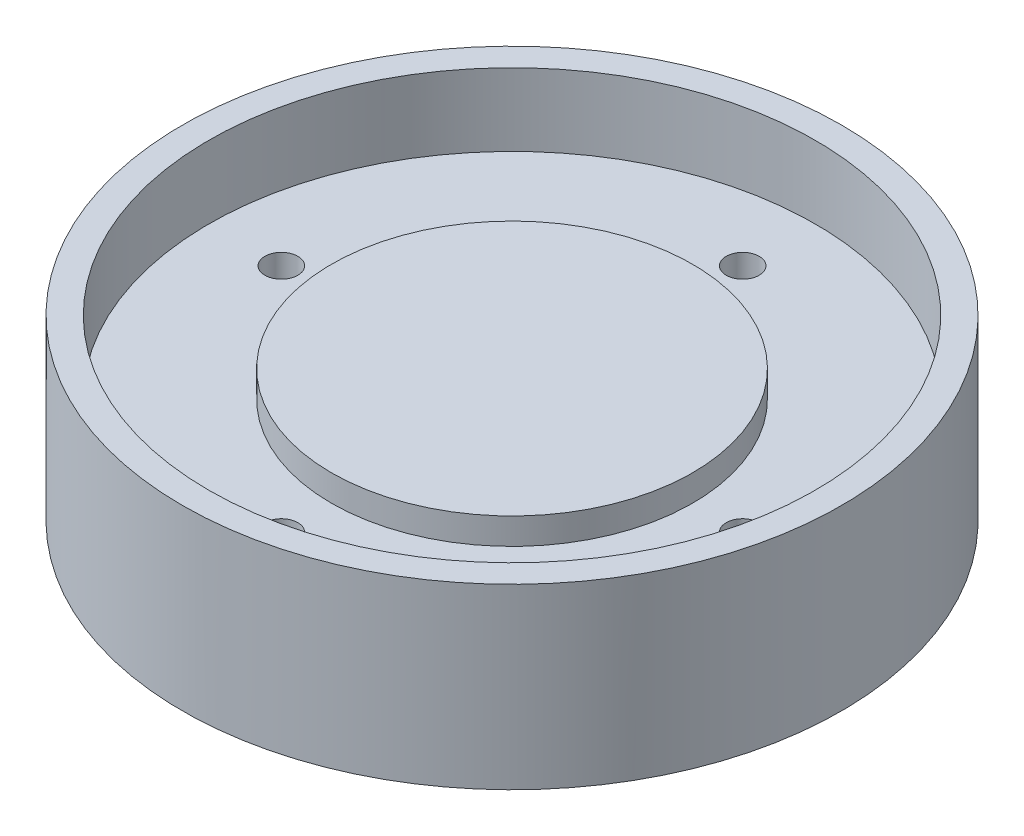
SolidWorks part; units mm, degrees
ref_plane "Front Plane" through (0, 0, 0) normal (0, 0, 1) x (1, 0, 0)
ref_plane "Top Plane" through (0, 0, 0) normal (0, 1, 0) x (1, 0, 0)
ref_plane "Right Plane" through (0, 0, 0) normal (1, 0, 0) x (0, 0, -1)
sketch "Sketch1" plane through (0, 0, 0) normal (0, 1, 0) x (1, 0, 0)
  circle A0 centre (0, 0) radius 50
  dimension "D1" = 100
extrude "Boss-Extrude2" add sketch "Sketch1" along normal blind 15
shell "Shell1" thickness 4
sketch "Sketch3" plane through (0, 4, 0) normal (0, 1, 0) x (1, 0, 0)
  circle A0 centre (0, 0) radius 27.405
  dimension "D1" = 54.81
extrude "Boss-Extrude3" add sketch "Sketch3" along normal blind 4
sketch "Sketch7" plane through (0, 8, 0) normal (0, 1, 0) x (1, 0, 0)
  line L0 (0, 52.4806) -> (0, -54.3438) construction
  line L1 (-67.9039, 0) -> (66.7998, 0) construction
  circle A0 centre (35, 0) radius 2.5
  circle A1 centre (0, 35) radius 2.5
  circle A2 centre (-35, 0) radius 2.5
  circle A3 centre (0, -35) radius 2.5
  dimension "D3" = 5
  dimension "D4" = 5
  dimension "D5" = 5
  dimension "D6" = 5
  dimension "D7" = 35
  dimension "D1" = 35
  dimension "D2" = 35
  dimension "D8" = 35
extrude "Cut-Extrude1" cut sketch "Sketch7" against normal blind 12
sketch "Sketch8" plane through (0, 0, 0) normal (0, -1, 0) x (-1, 0, 0)
  circle A0 centre (0, 0) radius 50
  circle A1 centre (0, 0) radius 48
  dimension "D1" = 100
  dimension "D2" = 2
extrude "Boss-Extrude5" add sketch "Sketch8" along normal blind 12
